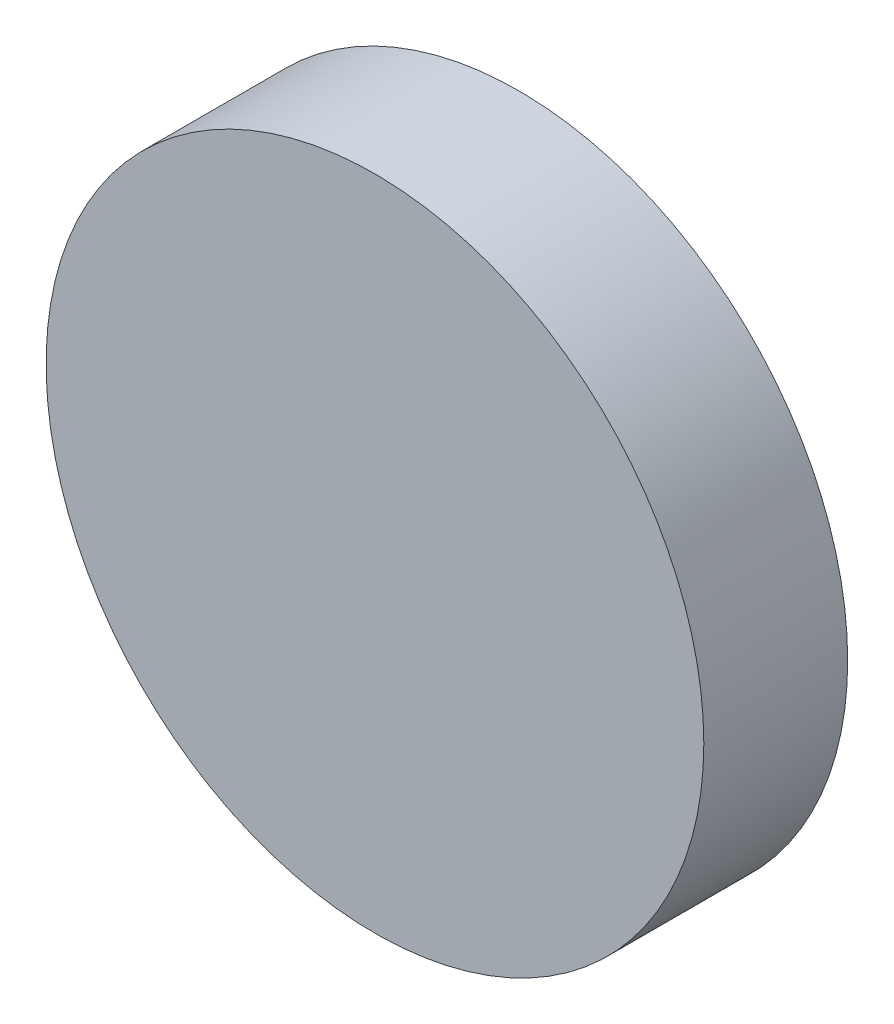
SolidWorks part; units mm, degrees
ref_plane "Front Plane" through (0, 0, 0) normal (0, 0, 1) x (1, 0, 0)
ref_plane "Top Plane" through (0, 0, 0) normal (0, 1, 0) x (1, 0, 0)
ref_plane "Right Plane" through (0, 0, 0) normal (1, 0, 0) x (0, 0, -1)
sketch "Sketch1" plane through (0, 0, 0) normal (0, 0, 1) x (1, 0, 0)
  circle A0 centre (16, 16) radius 16
  dimension "D1" = 32
extrude "Profile" add sketch "Sketch1" along normal blind 7
equation "\"Profile_Depth\"= 7mm"
equation "\"D1@Profile\" = \"Profile_Depth\""
equation "\"Profile_Sketch_1\"= 32mm"
equation "\"D1@Sketch1\" = \"Profile_Sketch_1\""
equation "\"EnvelopeWidth\"= 32mm"
equation "\"EnvelopeHeight\"= 32mm"
